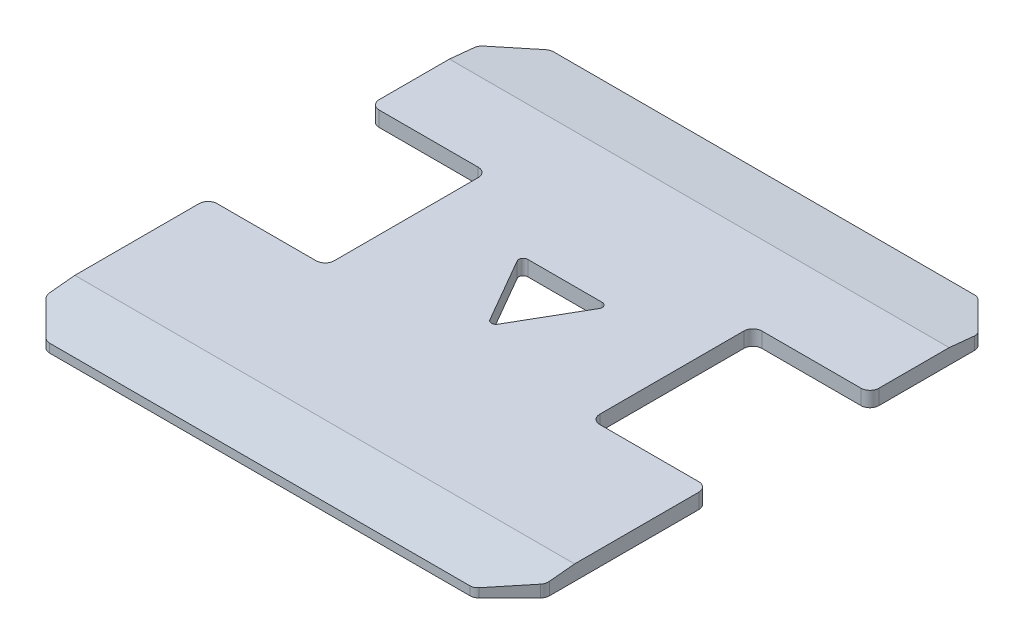
SolidWorks part; units mm, degrees
ref_plane "Front Plane" through (0, 0, 0) normal (0, 0, 1) x (1, 0, 0)
ref_plane "Bottom Plane" through (0, 0, 0) normal (0, 1, 0) x (1, 0, 0)
ref_plane "Right Plane" through (0, 0, 0) normal (1, 0, 0) x (0, 0, -1)
sketch "Sketch1" plane through (0, 0, 0) normal (0, 1, 0) x (1, 0, 0)
  line L1 (13.875, -14) -> (-13.875, -14)
  line L2 (13.875, -14) -> (13.875, 14)
  line L3 (13.875, 14) -> (-13.875, 14)
  line L4 (-13.875, -14) -> (-13.875, 14)
  line L5 (13.875, -14) -> (-13.875, 14) construction
  line L6 (13.875, 14) -> (-13.875, -14) construction
  point P0 (0, 0)
  dimension "D1" = 27.75
  dimension "D2" = 28
extrude "Boss-Extrude1" add sketch "Sketch1" along normal blind 0.84
sketch "Sketch2" plane through (0, 0, 0) normal (0, 1, 0) x (1, 0, 0)
  line L0 (0, -1000) -> (0, 49000) construction
  line L1 (-13.875, 14) -> (-13.875, -14) construction
  line L2 (-13.875, -3) -> (-7.375, -3)
  line L3 (-13.875, -3) -> (-13.875, 6)
  line L4 (-13.875, 6) -> (-7.375, 6)
  line L5 (-7.375, -3) -> (-7.375, 6)
  line L6 (-13.875, -3) -> (-7.375, 6) construction
  line L7 (-13.875, 6) -> (-7.375, -3) construction
  line L8 (13.875, 6) -> (7.375, -3) construction
  line L9 (13.875, -3) -> (7.375, 6) construction
  line L10 (7.375, -3) -> (7.375, 6)
  line L11 (13.875, 6) -> (7.375, 6)
  line L12 (13.875, -3) -> (13.875, 6)
  line L13 (13.875, -3) -> (7.375, -3)
  line L14 (-13.875, -14) -> (13.875, -14) construction
  line L15 (0, -1.3868) -> (2.5, 2.9434)
  line L16 (2.5, 2.9434) -> (-2.5, 2.9434)
  line L17 (-2.5, 2.9434) -> (0, -1.3868)
  line L18 (-1031.635, -3) -> (48968.365, -3) construction
  line L19 (-1031.5848, 6) -> (48968.4152, 6) construction
  circle A0 centre (0, 1.5) radius 1.4434 construction
  point P1 (-10.625, 1.5)
  point P14 (10.625, 1.5)
  dimension "D1" = 11
  dimension "D2" = 6.5
  dimension "D3" = 5
  dimension "D5" = 20
extrude "Cut-Extrude1" cut sketch "Sketch2" along normal up to next
chamfer "Chamfer1" distance 2 angle 45 4 edges at (-13.875, 0.42, 14) (-13.875, 0.42, -14) (13.875, 0.42, -14) (13.875, 0.42, 14)
chamfer "Chamfer2" distance 0.36 distance2 3.6 2 edges at (0, 0.84, -14) (0, 0.84, 14)
fillet "Fillet1" radius 0.5 16 edges at (-13.875, 0.42, 3) (-13.875, 0.42, -6) (13.875, 0.42, -6) (13.875, 0.42, 3) (7.375, 0.42, 3) (7.375, 0.42, -6) (-7.375, 0.42, -6) (-7.375, 0.42, 3) (-13.875, 0.34, -12) (-11.875, 0.24, -14) (11.875, 0.24, -14) (13.875, 0.34, -12) (13.875, 0.34, 12) (11.875, 0.24, 14) (-11.875, 0.24, 14) (-13.875, 0.34, 12)
fillet "Fillet2" radius 0.25 3 edges at (2.5, 0.42, -2.9434) (0, 0.42, 1.3868) (-2.5, 0.42, -2.9434)
